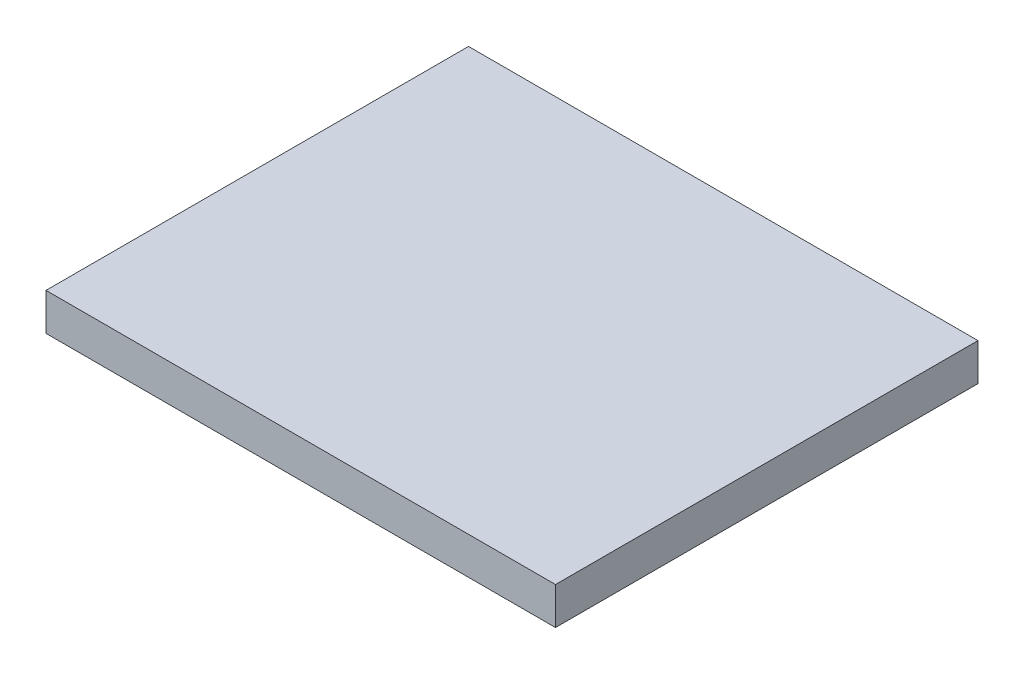
SolidWorks part; units mm, degrees
ref_plane "Front Plane" through (0, 0, 0) normal (0, 0, 1) x (1, 0, 0)
ref_plane "Top Plane" through (0, 0, 0) normal (0, 1, 0) x (1, 0, 0)
ref_plane "Right Plane" through (0, 0, 0) normal (1, 0, 0) x (0, 0, -1)
sketch "Sketch1" plane through (0, 0, 0) normal (0, 1, 0) x (1, 0, 0)
  line L1 (20.5, 17) -> (-20.5, 17)
  line L2 (20.5, 17) -> (20.5, -17)
  line L3 (20.5, -17) -> (-20.5, -17)
  line L4 (-20.5, 17) -> (-20.5, -17)
  line L5 (20.5, 17) -> (-20.5, -17) construction
  line L6 (20.5, -17) -> (-20.5, 17) construction
  point P0 (0, 0)
  dimension "D1" = 41
  dimension "D2" = 34
extrude "Boss-Extrude1" add sketch "Sketch1" along normal blind 3
